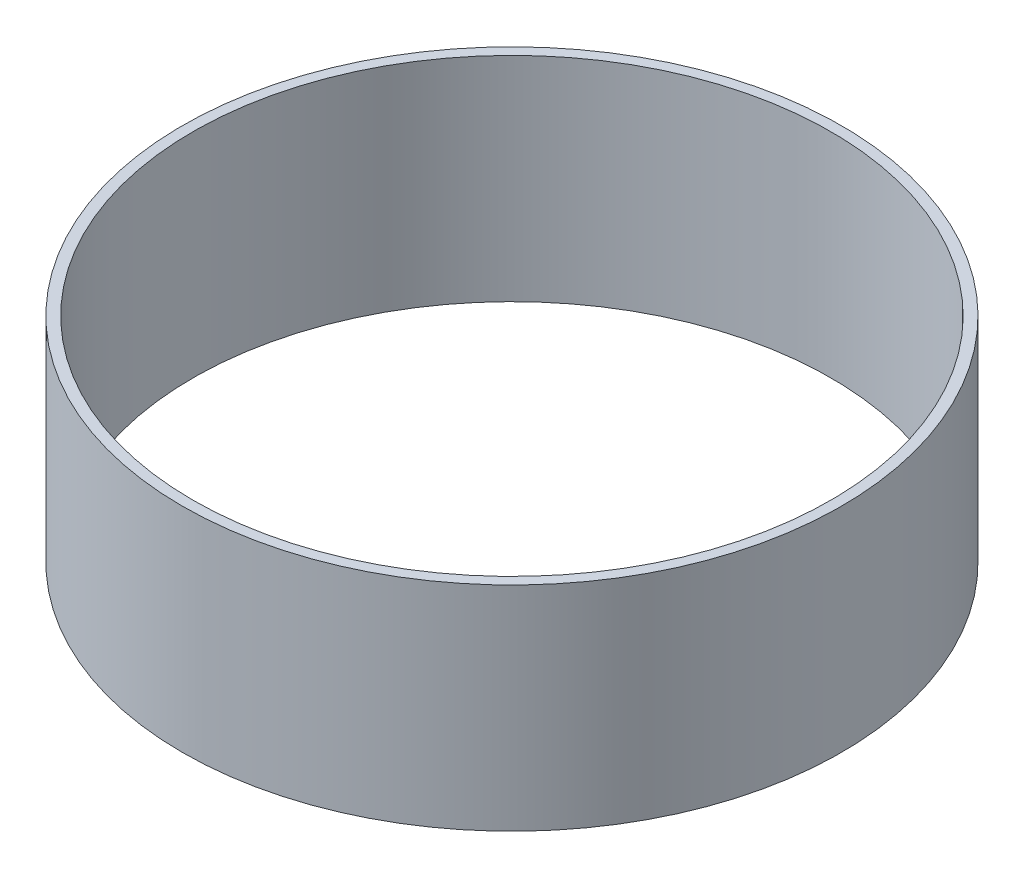
SolidWorks part; units mm, degrees
ref_plane "Front Plane" through (0, 0, 0) normal (0, 0, 1) x (1, 0, 0)
ref_plane "Top Plane" through (0, 0, 0) normal (0, 1, 0) x (1, 0, 0)
ref_plane "Right Plane" through (0, 0, 0) normal (1, 0, 0) x (0, 0, -1)
sketch "Sketch1" plane through (0, 0, 0) normal (0, 1, 0) x (1, 0, 0)
  circle A0 centre (0, 0) radius 78.5
  circle A1 centre (0, 0) radius 76
extrude "Boss-Extrude1" add sketch "Sketch1" along normal blind 50.8
